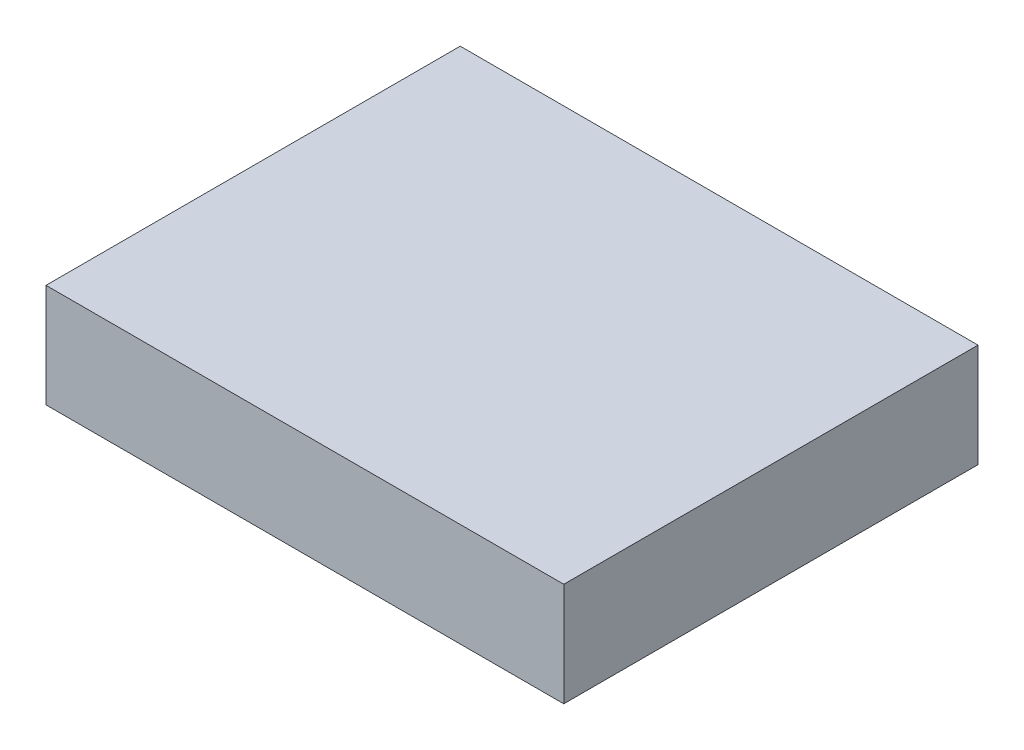
SolidWorks part; units mm, degrees
ref_plane "Front Plane" through (0, 0, 0) normal (0, 0, 1) x (1, 0, 0)
ref_plane "Top Plane" through (0, 0, 0) normal (0, 1, 0) x (1, 0, 0)
ref_plane "Right Plane" through (0, 0, 0) normal (1, 0, 0) x (0, 0, -1)
sketch "Sketch1" plane through (0, 0, 0) normal (0, 1, 0) x (1, 0, 0)
  line L1 (25, -20) -> (-25, -20)
  line L2 (25, -20) -> (25, 20)
  line L3 (25, 20) -> (-25, 20)
  line L4 (-25, -20) -> (-25, 20)
  line L5 (25, -20) -> (-25, 20) construction
  line L6 (25, 20) -> (-25, -20) construction
  point P0 (0, 0)
  dimension "D1" = 50
  dimension "D2" = 40
extrude "Boss-Extrude1" add sketch "Sketch1" along normal blind 10
